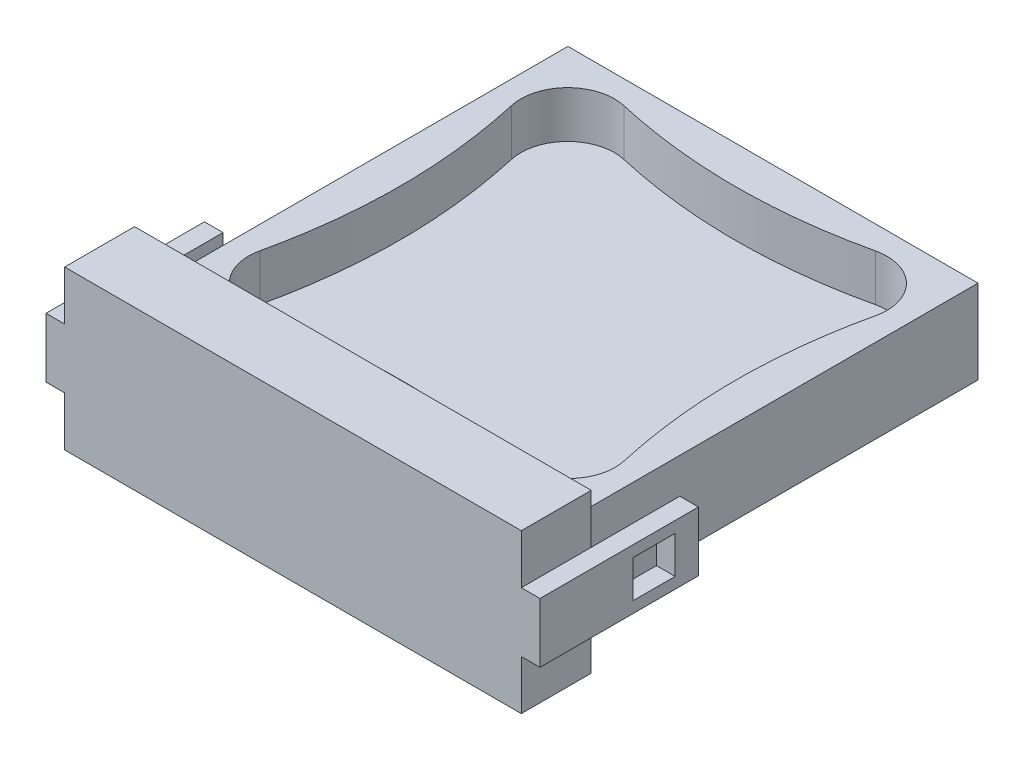
SolidWorks part; units mm, degrees
ref_plane "Front Plane" through (0, 0, 0) normal (0, 0, 1) x (1, 0, 0)
ref_plane "Top Plane" through (0, 0, 0) normal (0, 1, 0) x (1, 0, 0)
ref_plane "Right Plane" through (0, 0, 0) normal (1, 0, 0) x (0, 0, -1)
sketch "Sketch1" plane through (0, 0, 0) normal (0, 1, 0) x (1, 0, 0)
  line L1 (-22, -22) -> (22, -22)
  line L2 (-22, -22) -> (-22, 22)
  line L3 (-22, 22) -> (22, 22)
  line L4 (22, -22) -> (22, 22)
  line L5 (-22, -22) -> (22, 22) construction
  line L6 (-22, 22) -> (22, -22) construction
  point P0 (0, 0)
  dimension "D1" = 44
  dimension "D2" = 44
extrude "Boss-Extrude1" add sketch "Sketch1" along normal blind 9
sketch "Sketch2" plane through (0, 0, 22) normal (0, 0, 1) x (1, 0, 0)
  line L0 (0, 0) -> (0, 9) construction
  line L1 (-22, 9) -> (22, 9) construction
  line L2 (-22, 4.5) -> (22, 4.5) construction
  line L3 (-22, 9) -> (-22, 0) construction
  line L4 (22, 9) -> (22, 0) construction
  line L6 (-24.5, -4) -> (24.5, -4)
  line L7 (-24.5, -4) -> (-24.5, 13)
  line L8 (-24.5, 13) -> (24.5, 13)
  line L9 (24.5, -4) -> (24.5, 13)
  line L10 (-24.5, -4) -> (24.5, 13) construction
  line L11 (-24.5, 13) -> (24.5, -4) construction
  point P11 (0, 4.5)
  dimension "D1" = 2.5
  dimension "D2" = 4
extrude "Boss-Extrude2" add sketch "Sketch2" along normal blind 7.5
sketch "Sketch3" plane through (0, 9, 0) normal (0, 1, 0) x (1, 0, 0)
  line L0 (-18.0125, 0) -> (18.0125, 0) construction
  line L1 (0, -17.955) -> (0, 17.955) construction
  line L3 (-19.5325, -13.495) -> (19.5325, -13.495) construction
  line L4 (-19.5325, -13.495) -> (-19.5325, 13.495) construction
  line L5 (-19.5325, 13.495) -> (19.5325, 13.495) construction
  line L6 (19.5325, -13.495) -> (19.5325, 13.495) construction
  line L7 (-19.5325, -13.495) -> (19.5325, 13.495) construction
  line L8 (-19.5325, 13.495) -> (19.5325, -13.495) construction
  line L9 (-13.49, 19.495) -> (13.49, 19.495) construction
  line L10 (-13.49, 19.495) -> (-13.49, -19.495) construction
  line L11 (-13.49, -19.495) -> (13.49, -19.495) construction
  line L12 (13.49, 19.495) -> (13.49, -19.495) construction
  line L13 (-13.49, 19.495) -> (13.49, -19.495) construction
  line L14 (-13.49, -19.495) -> (13.49, 19.495) construction
  arc A0 (-19.5325, -13.495) -> (-13.49, -19.495) centre (-14.6292, -14.5996) ccw
  arc A1 (-19.5325, 13.495) -> (-13.49, 19.495) centre (-14.6292, 14.5996) cw
  arc A2 (13.49, 19.495) -> (19.5325, 13.495) centre (14.6117, 14.582) cw
  arc A3 (13.49, -19.495) -> (19.5325, -13.495) centre (14.6117, -14.582) ccw
  spline S0 degree 2 poles (19.5325, 13.495) (16.4925, 0) (19.5325, -13.495) knots 0 0 0 1 1 1
  spline S1 degree 3 poles (-19.5325, 13.495) (-18.5192, 8.9967) (-17.5058, 0) (-18.5192, -8.9967) (-19.5325, -13.495) knots 0 0 0 0 0.5 1 1 1 1
  spline S2 degree 3 poles (-13.49, 19.495) (-4.4967, 17.4417) (4.4967, 17.4417) (13.49, 19.495) knots 0 0 0 0 1 1 1 1
  spline S3 degree 3 poles (-13.49, -19.495) (-4.4967, -17.4417) (4.4967, -17.4417) (13.49, -19.495) knots 0 0 0 0 1 1 1 1
  point P0 (0, 0)
  point P3 (0, 0)
  point P4 (0, 0)
  point P8 (0, 0)
  dimension "D7" = 5.0262
  dimension "D8" = 5.0262
  dimension "D9" = 5.0394
  dimension "D10" = 5.0394
  dimension "D1" = 36.025
  dimension "D2" = 35.91
  dimension "D3" = 26.99
  dimension "D4" = 39.065
  dimension "D5" = 38.99
  dimension "D6" = 26.98
extrude "Cut-Extrude1" cut sketch "Sketch3" against normal blind 5
sketch "Sketch4" plane through (24.5, 0, 0) normal (1, 0, 0) x (0, 0, -1)
  line L0 (-29.5, 4.5) -> (-29.5, 7.7)
  line L1 (-29.5, -4) -> (-29.5, 13) construction
  line L2 (-29.5, 7.7) -> (-12.5, 7.7)
  line L3 (-12.5, 7.7) -> (-12.5, 1.3)
  line L4 (-12.5, 1.3) -> (-29.5, 1.3)
  line L5 (-29.5, 1.3) -> (-29.5, 4.5)
  line L6 (-29.5, 4.5) -> (-12.5, 4.5) construction
  line L8 (-19.5, 2.5) -> (-15, 2.5)
  line L9 (-19.5, 2.5) -> (-19.5, 6.5)
  line L10 (-19.5, 6.5) -> (-15, 6.5)
  line L11 (-15, 2.5) -> (-15, 6.5)
  line L12 (-19.5, 2.5) -> (-15, 6.5) construction
  line L13 (-19.5, 6.5) -> (-15, 2.5) construction
  point P4 (-17.25, 4.5)
  dimension "D1" = 3.2
  dimension "D2" = 3.2
  dimension "D3" = 17
  dimension "D4" = 2.5
  dimension "D5" = 4.5
  dimension "D6" = 4
extrude "Boss-Extrude3" add sketch "Sketch4" along normal blind 2
mirror "Mirror1" about plane through (0, 0, 0) normal (1, 0, 0) of "Boss-Extrude3"
